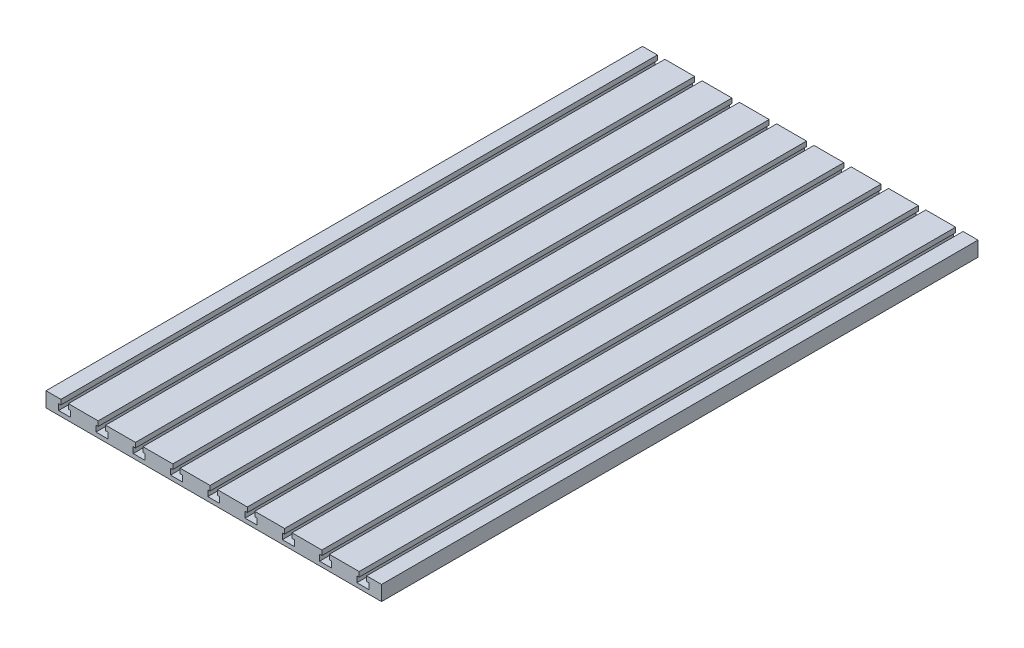
SolidWorks part; units mm, degrees
ref_plane "Front Plane" through (0, 0, 0) normal (0, 0, 1) x (1, 0, 0)
ref_plane "Top Plane" through (0, 0, 0) normal (0, 1, 0) x (1, 0, 0)
ref_plane "Right Plane" through (0, 0, 0) normal (1, 0, 0) x (0, 0, -1)
sketch "Sketch1" plane through (0, 0, 0) normal (0, 0, 1) x (1, 0, 0)
  line L1 (0, 0) -> (-450, 0)
  line L2 (0, 0) -> (0, 20)
  line L3 (0, 20) -> (-450, 20)
  line L4 (-450, 0) -> (-450, 20)
  dimension "D1" = 450
  dimension "D2" = 20
extrude "Boss-Extrude1" add sketch "Sketch1" along normal blind 800
sketch "Sketch2" plane through (0, 0, 800) normal (0, 0, 1) x (1, 0, 0)
  line L0 (-430, 20) -> (-430, 13.5)
  line L1 (0, 20) -> (-450, 20) construction
  line L2 (-430, 13.5) -> (-433, 13.5)
  line L3 (-433, 13.5) -> (-433, 5.5)
  line L4 (-433, 5.5) -> (-417, 5.5)
  line L5 (-425, 5.5) -> (-425, 20) construction
  line L6 (-417, 13.5) -> (-417, 5.5)
  line L7 (-420, 13.5) -> (-417, 13.5)
  line L8 (-420, 20) -> (-420, 13.5)
  line L9 (-380, 20) -> (-380, 13.5)
  line L10 (-380, 13.5) -> (-383, 13.5)
  line L11 (-383, 13.5) -> (-383, 5.5)
  line L12 (-383, 5.5) -> (-367, 5.5)
  line L13 (-367, 13.5) -> (-367, 5.5)
  line L14 (-370, 13.5) -> (-367, 13.5)
  line L15 (-370, 20) -> (-370, 13.5)
  line L16 (-380, 20) -> (-370, 20)
  line L17 (-375, 5.5) -> (-375, 20) construction
  line L18 (-330, 20) -> (-330, 13.5)
  line L19 (-330, 13.5) -> (-333, 13.5)
  line L20 (-333, 13.5) -> (-333, 5.5)
  line L21 (-333, 5.5) -> (-317, 5.5)
  line L22 (-317, 13.5) -> (-317, 5.5)
  line L23 (-320, 13.5) -> (-317, 13.5)
  line L24 (-320, 20) -> (-320, 13.5)
  line L25 (-330, 20) -> (-320, 20)
  line L26 (-325, 5.5) -> (-325, 20) construction
  line L27 (-280, 20) -> (-280, 13.5)
  line L28 (-280, 13.5) -> (-283, 13.5)
  line L29 (-283, 13.5) -> (-283, 5.5)
  line L30 (-283, 5.5) -> (-267, 5.5)
  line L31 (-267, 13.5) -> (-267, 5.5)
  line L32 (-270, 13.5) -> (-267, 13.5)
  line L33 (-270, 20) -> (-270, 13.5)
  line L34 (-280, 20) -> (-270, 20)
  line L35 (-275, 5.5) -> (-275, 20) construction
  line L36 (-230, 20) -> (-230, 13.5)
  line L37 (-230, 13.5) -> (-233, 13.5)
  line L38 (-233, 13.5) -> (-233, 5.5)
  line L39 (-233, 5.5) -> (-217, 5.5)
  line L40 (-217, 13.5) -> (-217, 5.5)
  line L41 (-220, 13.5) -> (-217, 13.5)
  line L42 (-220, 20) -> (-220, 13.5)
  line L43 (-230, 20) -> (-220, 20)
  line L44 (-225, 5.5) -> (-225, 20) construction
  line L45 (-180, 20) -> (-180, 13.5)
  line L46 (-180, 13.5) -> (-183, 13.5)
  line L47 (-183, 13.5) -> (-183, 5.5)
  line L48 (-183, 5.5) -> (-167, 5.5)
  line L49 (-167, 13.5) -> (-167, 5.5)
  line L50 (-170, 13.5) -> (-167, 13.5)
  line L51 (-170, 20) -> (-170, 13.5)
  line L52 (-180, 20) -> (-170, 20)
  line L53 (-175, 5.5) -> (-175, 20) construction
  line L54 (-130, 20) -> (-130, 13.5)
  line L55 (-130, 13.5) -> (-133, 13.5)
  line L56 (-133, 13.5) -> (-133, 5.5)
  line L57 (-133, 5.5) -> (-117, 5.5)
  line L58 (-117, 13.5) -> (-117, 5.5)
  line L59 (-120, 13.5) -> (-117, 13.5)
  line L60 (-120, 20) -> (-120, 13.5)
  line L61 (-130, 20) -> (-120, 20)
  line L62 (-125, 5.5) -> (-125, 20) construction
  line L63 (-80, 20) -> (-80, 13.5)
  line L64 (-80, 13.5) -> (-83, 13.5)
  line L65 (-83, 13.5) -> (-83, 5.5)
  line L66 (-83, 5.5) -> (-67, 5.5)
  line L67 (-67, 13.5) -> (-67, 5.5)
  line L68 (-70, 13.5) -> (-67, 13.5)
  line L69 (-70, 20) -> (-70, 13.5)
  line L70 (-80, 20) -> (-70, 20)
  line L71 (-75, 5.5) -> (-75, 20) construction
  line L72 (-30, 20) -> (-30, 13.5)
  line L73 (-30, 13.5) -> (-33, 13.5)
  line L74 (-33, 13.5) -> (-33, 5.5)
  line L75 (-33, 5.5) -> (-17, 5.5)
  line L76 (-17, 13.5) -> (-17, 5.5)
  line L77 (-20, 13.5) -> (-17, 13.5)
  line L78 (-20, 20) -> (-20, 13.5)
  line L79 (-30, 20) -> (-20, 20)
  line L80 (-25, 5.5) -> (-25, 20) construction
  line L81 (-450, 20) -> (-450, 0) construction
  line L82 (-430, 20) -> (-420, 20)
  line L83 (20, 20) -> (20, 13.5)
  line L84 (20, 13.5) -> (17, 13.5)
  line L85 (17, 13.5) -> (17, 5.5)
  line L86 (17, 5.5) -> (33, 5.5)
  line L87 (33, 13.5) -> (33, 5.5)
  line L88 (30, 13.5) -> (33, 13.5)
  line L89 (30, 20) -> (30, 13.5)
  line L90 (20, 20) -> (30, 20)
  line L91 (25, 5.5) -> (25, 20) construction
  dimension "D1" = 5
  dimension "D2" = 6.5
  dimension "D3" = 8
  dimension "D4" = 8
  dimension "D6" = 25
  dimension "D5" = 10
extrude "Cut-Extrude1" cut sketch "Sketch2" against normal through all
